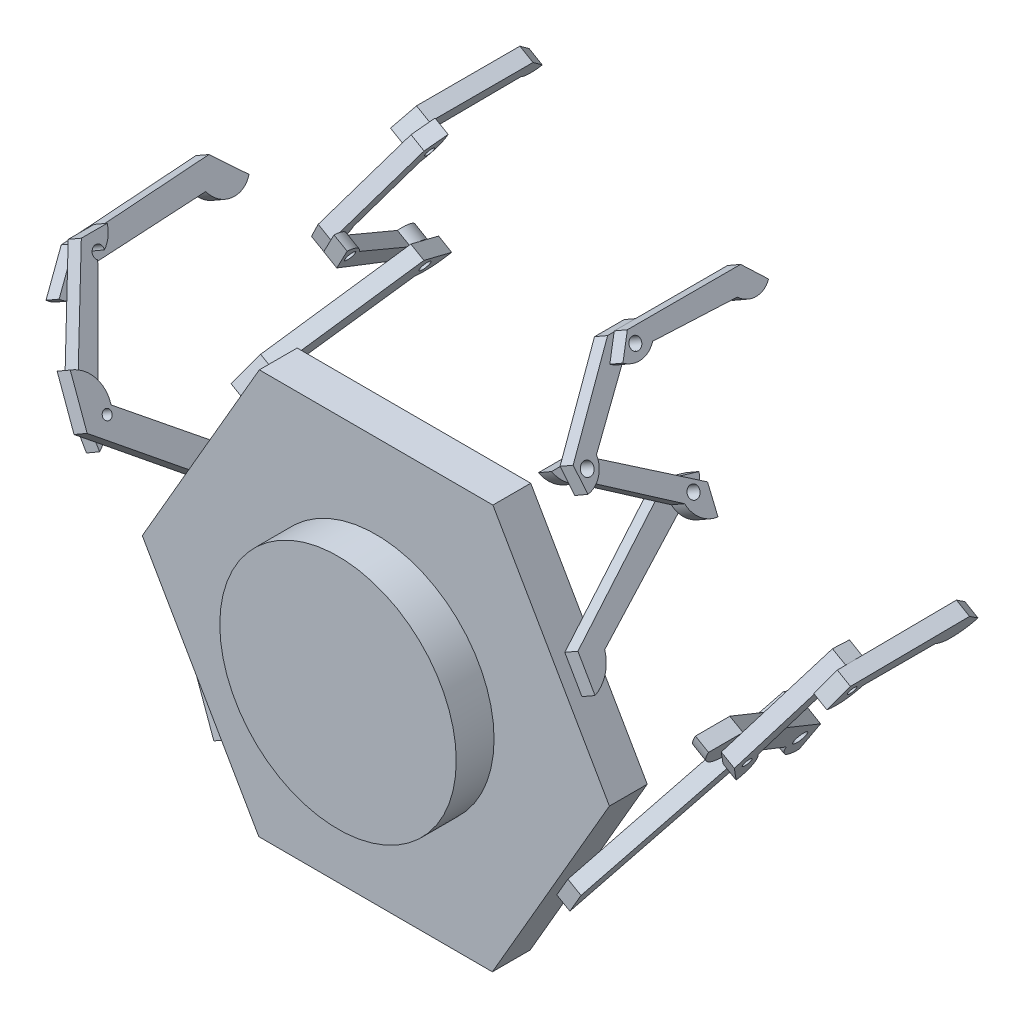
SolidWorks part; units mm, degrees
ref_plane "Front Plane" through (0, 0, 0) normal (0, 0, 1) x (1, 0, 0)
ref_plane "Top Plane" through (0, 0, 0) normal (0, 1, 0) x (1, 0, 0)
ref_plane "Right Plane" through (0, 0, 0) normal (1, 0, 0) x (0, 0, -1)
sketch "Sketch1" plane through (0, 0, 0) normal (0, 0, 1) x (1, 0, 0)
  line L17 (15.4724, 26.7163) -> (-15.4008, 26.7576)
  line L18 (-15.4008, 26.7576) -> (-30.8732, 0.0413)
  line L19 (-30.8732, 0.0413) -> (-15.4724, -26.7163)
  line L20 (-15.4724, -26.7163) -> (15.4008, -26.7576)
  line L21 (15.4008, -26.7576) -> (30.8732, -0.0413)
  line L22 (30.8732, -0.0413) -> (15.4724, 26.7163)
  circle A1 centre (0, 0) radius 26.737 construction
extrude "Boss-Extrude1" add sketch "Sketch1" along normal blind 5
sketch "Sketch4" plane through (23.137, -13.3995, 0) normal (0.8654, -0.5012, 0) x (0, 0, -1)
  line L0 (-2.7485, 0) -> (15.8375, 19.8665)
  line L1 (15.8375, 19.8665) -> (18.1947, 17.9525)
  line L2 (14.6997, 15.5791) -> (-2.7485, -2.9311)
  line L3 (-2.7485, -2.9311) -> (-2.7485, 0)
  arc A0 (18.1947, 17.9525) -> (14.6997, 15.5791) centre (12.5027, 22.5743) cw
extrude "Boss-Extrude6" add sketch "Sketch4" along normal blind 2
sketch "Sketch6" plane through (24.8677, -14.4018, 0) normal (0.8654, -0.5012, 0) x (0, 0, -1)
  line L0 (18.1947, 17.9525) -> (2.2265, 29.3344)
  line L1 (2.2265, 29.3344) -> (-2.3244, 29.3344)
  line L2 (18.1947, 17.9525) -> (17.3952, 13.9075)
  line L3 (14.1678, 16.9269) -> (2.2265, 25.3082)
  arc A0 (17.3952, 13.9075) -> (14.1678, 16.9269) centre (17.2912, 17.0309) cw
  arc A1 (-2.3244, 29.3344) -> (2.2265, 25.3082) centre (1.9641, 29.5967) ccw
extrude "Boss-Extrude7" add sketch "Sketch6" along normal blind 2
sketch "Sketch7" plane through (26.5984, -15.4041, 0) normal (0.8654, -0.5012, 0) x (0, 0, -1)
  line L0 (0.4622, 27.1318) -> (9.0064, 39.42)
  line L1 (9.0064, 39.42) -> (11.3973, 39.1273)
  line L2 (0.4622, 27.1318) -> (2.7134, 23.1031)
  line L3 (9.837, 37.0641) -> (3.5608, 27.1318)
  arc A0 (2.7134, 23.1031) -> (3.5608, 27.1318) centre (1.1228, 25.5412) ccw
  arc A1 (11.3973, 39.1273) -> (9.837, 37.0641) centre (9.5856, 38.8758) cw
extrude "Boss-Extrude8" add sketch "Sketch7" along normal blind 2
sketch "Sketch8" plane through (28.3291, -16.4064, 0) normal (0.8654, -0.5012, 0) x (0, 0, -1)
  line L0 (7.96, 39.3319) -> (23.504, 39.7244)
  line L1 (23.504, 39.7244) -> (25.6468, 37.6872)
  line L2 (7.96, 39.3319) -> (6.4078, 36.2239)
  line L3 (7.96, 39.3319) -> (10.5952, 37.3566) construction
  line L4 (23.504, 39.7244) -> (20.2518, 37.3566) construction
  line L5 (10.5952, 37.3566) -> (20.2518, 37.3566)
  arc A0 (10.5952, 37.3566) -> (6.4078, 36.2239) centre (7.7768, 39.4693) cw
  arc A1 (25.6468, 37.6872) -> (20.2518, 37.3566) centre (22.7922, 40.086) cw
extrude "Boss-Extrude9" add sketch "Sketch8" along normal blind 2
sketch "Sketch9" plane through (-23.1728, -13.3375, 0) normal (-0.8667, -0.4988, 0) x (0, 0, 1)
  line L0 (3.4898, 0.8289) -> (-11.5004, 16.3176)
  line L1 (-11.5004, 16.3176) -> (-16.6407, 14.7914)
  line L2 (3.4898, 0.8289) -> (4.3898, -5.7763)
  line L3 (-11.5004, 12.3514) -> (0, -0.9719)
  line L4 (0, 15.4366) -> (0, -15.4366) construction
  arc A0 (4.3898, -5.7763) -> (0, -0.9719) centre (4.3564, -1.3992) cw
  arc A1 (-16.6407, 14.7914) -> (-11.5004, 12.3514) centre (-12.6462, 16.5721) ccw
extrude "Boss-Extrude11" add sketch "Sketch9" along normal blind 2
sketch "Sketch10" plane through (-24.9062, -14.3352, 0) normal (-0.8667, -0.4988, 0) x (0, 0, 1)
  line L0 (-10.8587, 12.6241) -> (5.2144, 26.1402)
  line L1 (5.2144, 26.1402) -> (4.3916, 32.2663)
  line L2 (-10.8587, 12.6241) -> (-15.8707, 12.6241)
  line L3 (1.4413, 27.3689) -> (-11.5793, 16.4764)
  arc A0 (-15.8707, 12.6241) -> (-11.5793, 16.4764) centre (-12.0537, 12.6884) cw
  arc A1 (4.3916, 32.2663) -> (1.4413, 27.3689) centre (5.6257, 28.1855) ccw
extrude "Boss-Extrude13" add sketch "Sketch10" along normal blind 2
sketch "Sketch11" plane through (-26.6396, -15.3328, 0) normal (-0.8667, -0.4988, 0) x (0, 0, 1)
  line L0 (3.1813, 29.2558) -> (-3.7804, 42.2453)
  line L1 (3.1813, 29.2558) -> (3.1813, 23.4502)
  line L2 (-3.7804, 42.2453) -> (-7.1981, 42.2453)
  line L3 (-4.6827, 39.6989) -> (1.4413, 27.3689)
  arc A0 (-7.1981, 42.2453) -> (-4.6827, 39.6989) centre (-4.0689, 42.8208) ccw
  arc A1 (3.1813, 23.4502) -> (1.4413, 27.3689) centre (4.8173, 26.5223) cw
extrude "Boss-Extrude14" add sketch "Sketch11" along normal blind 2
sketch "Sketch12" plane through (-28.373, -16.3305, 0) normal (-0.8667, -0.4988, 0) x (0, 0, 1)
  line L0 (-4.2666, 41.5835) -> (-22.5358, 42.5455)
  line L1 (-4.2666, 41.5835) -> (-0.2995, 37.6739)
  line L2 (-22.5358, 42.5455) -> (-26.0342, 38.9386)
  line L3 (-4.8958, 38.9386) -> (-20.6281, 39.5986)
  arc A0 (-26.0342, 38.9386) -> (-20.6281, 39.5986) centre (-23.5508, 41.0675) ccw
  arc A1 (-0.2995, 37.6739) -> (-4.8958, 38.9386) centre (-2.2421, 39.5986) cw
extrude "Boss-Extrude15" add sketch "Sketch12" along normal blind 2
sketch "Sketch14" plane through (-26.6396, -15.3328, 0) normal (-0.8667, -0.4988, 0) x (0, 0, 1)
  circle A0 centre (-12.5819, 14.4117) radius 0.8438
extrude "Cut-Extrude1" cut sketch "Sketch14" against normal blind 7 and the other way blind 17 contours A0
sketch "Sketch15" plane through (-28.373, -16.3305, 0) normal (-0.8667, -0.4988, 0) x (0, 0, 1)
  circle A0 centre (2.2653, 26.742) radius 0.5913
extrude "Cut-Extrude2" cut sketch "Sketch15" against normal blind 9 contours A0
sketch "Sketch16" plane through (-30.1063, -17.3282, 0) normal (-0.8667, -0.4988, 0) x (0, 0, 1)
  circle A0 centre (-5.0531, 40.2697) radius 0.7452
extrude "Cut-Extrude3" cut sketch "Sketch16" against normal blind 9
sketch "Sketch17" plane through (28.3291, -16.4064, 0) normal (0.8654, -0.5012, 0) x (0, 0, -1)
  circle A0 centre (2.4122, 26.6276) radius 0.5941
extrude "Cut-Extrude4" cut sketch "Sketch17" against normal blind 9
sketch "Sketch18" plane through (26.5984, -15.4041, 0) normal (0.8654, -0.5012, 0) x (0, 0, -1)
  circle A0 centre (15.853, 17.2553) radius 0.9004
extrude "Cut-Extrude5" cut sketch "Sketch18" against normal blind 9
sketch "Sketch19" plane through (30.0598, -17.4088, 0) normal (0.8654, -0.5012, 0) x (0, 0, -1)
  circle A0 centre (9.0106, 37.7005) radius 0.5725
extrude "Cut-Extrude6" cut sketch "Sketch19" against normal blind 9
sketch "Sketch20" plane through (0, 0, 5) normal (0, 0, 1) x (1, 0, 0)
  circle A0 centre (0, 0) radius 15.6287
extrude "Boss-Extrude19" add sketch "Sketch20" along normal blind 5
sketch "Sketch22" plane through (-23.137, 13.3995, 0) normal (-0.8654, 0.5012, 0) x (0, 0, 1)
  line L0 (1.6707, 12.5846) -> (-14.4892, 19.967)
  line L1 (-14.4892, 19.967) -> (-19.4079, 17.4669)
  line L2 (1.6707, 12.5846) -> (3.6396, 8.7109)
  line L3 (0, 15.4366) -> (0, -15.4366) construction
  line L4 (0, 10.2076) -> (-14.9261, 16.6799)
  arc A0 (3.6396, 8.7109) -> (0, 10.2076) centre (2.7456, 11.7105) cw
  arc A1 (-19.4079, 17.4669) -> (-14.9261, 16.6799) centre (-16.2924, 22.0539) ccw
  point P6 (0, 10.4736)
  point P11 (0, 0)
  point P12 (0, 0)
  point P13 (-9.8694, 16.2508)
  point P14 (0, 10.8926)
  point P15 (0, 0)
  point P16 (0, 0)
  point P17 (-14.5372, 20.8354)
  point P18 (-11.3869, 19.4536)
  point P19 (0, 13.2427)
  point P20 (-15.5642, 23.6382)
  point P21 (-16.9487, 21.7357)
  point P22 (-12.5342, 19.5462)
  point P23 (-18.9439, 16.4167)
  point P24 (-14.9261, 20.1666)
  point P25 (-14.9261, 16.1896)
  point P26 (2.2021, 12.3418)
  point P27 (0, 10.2076)
  point P28 (3.6396, 8.7109)
  point P29 (0, 0)
  point P30 (0, 0)
  point P31 (-14.9261, 16.6799)
  point P32 (0, 0)
  point P33 (0, 0)
  point P34 (-19.4079, 17.4669)
extrude "Boss-Extrude21" add sketch "Sketch22" along normal blind 2
sketch "Sketch23" plane through (-24.8677, 14.4018, 0) normal (-0.8654, 0.5012, 0) x (0, 0, 1)
  line L0 (-14.4239, 17.0626) -> (-1.7402, 25.8801)
  line L1 (-1.7402, 25.8801) -> (-1.4015, 29.2783)
  line L2 (-14.4239, 17.0626) -> (-18.1086, 17.1904)
  line L3 (-4.1659, 26.9923) -> (-14.826, 19.2046)
  arc A0 (-18.1086, 17.1904) -> (-14.826, 19.2046) centre (-15.4299, 16.5068) cw
  arc A1 (-1.4015, 29.2783) -> (-4.1659, 26.9923) centre (-0.802, 25.739) ccw
  point P8 (0, 0)
  point P9 (-18.1086, 17.1849)
  point P10 (0, 0)
  point P11 (-6.5862, 25.8801)
  point P12 (-1.7402, 25.725)
  point P13 (-2.6146, 29.0958)
  point P14 (-5.4347, 26.3272)
  point P15 (-1.7402, 29.1008)
  point P16 (-4.1659, 26.9923)
  point P17 (-1.4015, 29.2783)
extrude "Boss-Extrude22" add sketch "Sketch23" along normal blind 2
sketch "Sketch25" plane through (-26.5984, 15.4041, 0) normal (-0.8654, 0.5012, 0) x (0, 0, 1)
  line L0 (-1.6797, 27.9912) -> (-8.2674, 39.3243)
  line L1 (-1.6797, 27.9912) -> (-2.0671, 25.4422)
  line L2 (-8.2674, 39.3243) -> (-11.0249, 40.1697)
  line L3 (-9.0673, 36.6828) -> (-4.3738, 28.4007)
  arc A0 (-2.0671, 25.4422) -> (-4.3738, 28.4007) centre (-1.7412, 28.0748) cw
  arc A1 (-11.0249, 40.1697) -> (-9.0673, 36.6828) centre (-7.3387, 39.9463) ccw
  point P8 (-9.5367, 36.7971)
extrude "Boss-Extrude23" add sketch "Sketch25" along normal blind 2 contours L3 A0 L1 L0 L2 A1
sketch "Sketch26" plane through (-28.3291, 16.4064, 0) normal (-0.8654, 0.5012, 0) x (0, 0, 1)
  line L0 (-10.4486, 39.8793) -> (-24.1145, 39.8793)
  line L1 (-10.4486, 39.8793) -> (-8.1579, 37.5885)
  line L2 (-24.1145, 39.8793) -> (-26.5667, 37.427)
  line L3 (-10.9343, 37.3259) -> (-23.6977, 37.5891)
  arc A0 (-26.5667, 37.427) -> (-23.6977, 37.5891) centre (-25.2378, 39.3767) ccw
  arc A1 (-8.1579, 37.5885) -> (-10.9343, 37.3259) centre (-9.6649, 38.7134) cw
  point P8 (-11.0426, 37.4334)
  point P9 (-10.1765, 39.747)
  point P10 (0, 0)
  point P11 (-24.3866, 39.6071)
extrude "Boss-Extrude24" add sketch "Sketch26" along normal blind 2
sketch "Sketch28" plane through (23.1728, 13.3375, 0) normal (0.8667, 0.4988, 0) x (0, 0, -1)
  line L0 (-3.3932, -0.3919) -> (13.3939, 9.7522)
  line L1 (13.3939, 9.7522) -> (17.1994, 8.8135)
  line L2 (-3.3932, -0.3919) -> (-3.3932, -4.9353)
  line L3 (13.3939, 6.4338) -> (-0.433, -1.5588)
  arc A0 (-3.3932, -4.9353) -> (-0.433, -1.5588) centre (-4.6508, -0.8468) ccw
  arc A1 (17.1994, 8.8135) -> (13.3939, 6.4338) centre (14.1292, 9.4907) cw
  point P8 (-0.433, -1.5588)
  point P9 (13.3939, 6.4338)
  point P10 (-3.3932, -4.9353)
extrude "Boss-Extrude26" add sketch "Sketch28" along normal blind 2
sketch "Sketch29" plane through (24.9062, 14.3352, 0) normal (0.8667, 0.4988, 0) x (0, 0, -1)
  line L0 (16.2238, 8.0721) -> (3.5655, 16.4856)
  line L1 (16.2238, 8.0721) -> (15.8934, 4.6229)
  line L2 (3.5655, 16.4856) -> (-0.1945, 16.4856)
  line L3 (12.8345, 7.3515) -> (3.132, 13.9461)
  arc A0 (15.8934, 4.6229) -> (12.8345, 7.3515) centre (16.2238, 8.0721) cw
  arc A1 (-0.1945, 16.4856) -> (3.132, 13.9461) centre (3.5655, 17.9623) ccw
  point P0 (16.2238, 8.0721)
  point P8 (14.8781, 5.5139)
  point P9 (13.1386, 7.6893)
  point P10 (2.3822, 15.6143)
  point P11 (3.4115, 16.734)
  point P12 (0.9521, 16.2674)
  point P13 (4.0523, 14.142)
  point P14 (0, 0)
  point P15 (15.3696, 5.5322)
  point P16 (0, 16.4237)
  point P17 (3.8378, 14.3524)
  point P18 (12.2257, 8.2212)
  point P19 (14.5473, 5.3822)
  point P20 (12.5885, 7.8878)
  point P21 (15.1055, 5.804)
  point P22 (12.2477, 7.2995)
  point P23 (14.2318, 4.5193)
  point P24 (11.3351, 7.7778)
  point P25 (11.7585, 7.59)
  point P26 (14.7135, 8.053)
  point P27 (15.7553, 5.5308)
  point P28 (15.0625, 9.3406)
extrude "Boss-Extrude28" add sketch "Sketch29" along normal blind 2
sketch "Sketch31" plane through (26.6396, 15.3328, 0) normal (0.8667, 0.4988, 0) x (0, 0, -1)
  line L0 (0.9436, 16.5076) -> (10.0857, 25.7097)
  line L1 (0.9436, 16.5076) -> (1.3205, 13.3472)
  line L2 (10.0857, 25.7097) -> (14.0025, 25.7097)
  line L3 (16.2238, 8.0721) -> (3.5655, 16.4856) construction
  line L4 (11.3175, 23.4572) -> (3.9026, 16.2616)
  arc A0 (1.3205, 13.3472) -> (3.9026, 16.2616) centre (1.0252, 16.2099) ccw
  arc A1 (14.0025, 25.7097) -> (11.3175, 23.4572) centre (11.2941, 26.2116) cw
  point P10 (10.6162, 25.6423)
  point P11 (13.4485, 26.4386)
  point P12 (10.3308, 25.7097)
  point P13 (10.6213, 23.592)
  point P14 (3.5939, 16.4668)
  point P15 (3.9026, 16.2099)
extrude "Boss-Extrude30" add sketch "Sketch31" along normal blind 2
sketch "Sketch32" plane through (28.373, 16.3305, 0) normal (0.8667, 0.4988, 0) x (0, 0, -1)
  line L5 (10.9987, 25.7802) -> (25.9692, 25.7802)
  line L6 (25.9692, 25.7802) -> (28.3782, 23.1981)
  line L9 (13.2547, 23.5869) -> (24.2319, 23.1981)
  line L10 (10.9987, 25.7802) -> (9.1269, 23.1981)
  arc A3 (28.3782, 23.1981) -> (24.2319, 23.1981) centre (26.3051, 25.2358) cw
  arc A4 (9.1269, 23.1981) -> (13.2547, 23.5869) centre (10.9766, 25.6662) ccw
  point P6 (13.408, 23.8953)
  point P7 (0, 0)
  point P10 (13.2547, 23.5869)
extrude "Boss-Extrude31" add sketch "Sketch32" along normal blind 2
sketch "Sketch33" plane through (26.6396, 15.3328, 0) normal (0.8667, 0.4988, 0) x (0, 0, -1)
  circle A0 centre (14.2911, 7.8884) radius 0.7736
  point P2 (0, 0)
extrude "Cut-Extrude8" cut sketch "Sketch33" against normal blind 9
sketch "Sketch34" plane through (28.373, 16.3305, 0) normal (0.8667, 0.4988, 0) x (0, 0, -1)
  circle A0 centre (2.3111, 15.5277) radius 0.8189
extrude "Cut-Extrude10" cut sketch "Sketch34" against normal blind 7 contours A0
sketch "Sketch36" plane through (30.1063, 17.3282, 0) normal (0.8667, 0.4988, 0) x (0, 0, -1)
  circle A0 centre (11.2979, 24.2496) radius 0.7625
extrude "Cut-Extrude11" cut sketch "Sketch36" against normal blind 11
sketch "Sketch37" plane through (-30.0598, 17.4088, 0) normal (-0.8654, 0.5012, 0) x (0, 0, 1)
  circle A0 centre (-9.6693, 37.9999) radius 0.6051
  point P2 (0, 0)
extrude "Cut-Extrude12" cut sketch "Sketch37" against normal blind 11 contours A0
sketch "Sketch38" plane through (-28.3291, 16.4064, 0) normal (-0.8654, 0.5012, 0) x (0, 0, 1)
  circle A0 centre (-2.8401, 27.1876) radius 0.6753
extrude "Cut-Extrude13" cut sketch "Sketch38" against normal blind 11
sketch "Sketch39" plane through (-26.5984, 15.4041, 0) normal (-0.8654, 0.5012, 0) x (0, 0, 1)
  circle A0 centre (-15.6021, 18.0067) radius 0.7283
extrude "Cut-Extrude14" cut sketch "Sketch39" against normal blind 11 contours A0
